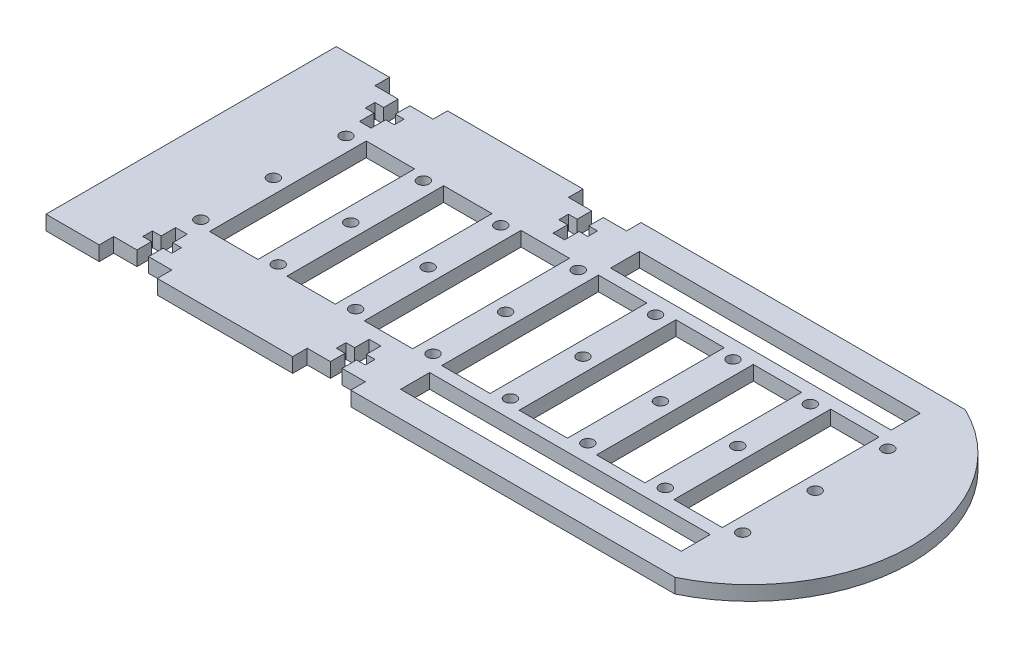
SolidWorks part; units mm, degrees
ref_plane "Front Plane" through (0, 0, 0) normal (0, 0, 1) x (1, 0, 0)
ref_plane "Top Plane" through (0, 0, 0) normal (0, 1, 0) x (1, 0, 0)
ref_plane "Right Plane" through (0, 0, 0) normal (1, 0, 0) x (0, 0, -1)
sketch "Sketch2" plane through (0, 0, 0) normal (0, 1, 0) x (1, 0, 0)
  line L0 (-93.98, 0) -> (93.98, 0) construction
  line L2 (-93.98, 38.1) -> (-93.98, -38.1)
  line L3 (-93.98, -38.1) -> (71.12, -38.1)
  line L9 (-93.98, 38.1) -> (71.12, 38.1)
  arc A8 (71.12, 38.1) -> (71.12, -38.1) centre (52.8038, 0) cw
  dimension "D1" = 165.1
  dimension "D2" = 76.2
extrude "Boss-Extrude1" add sketch "Sketch2" along normal blind 3.81
sketch "Sketch4" plane through (0, 0, 0) normal (0, -1, 0) x (-1, 0, 0)
  line L0 (46.99, -35.56) -> (46.99, -29.7953) construction
  line L2 (93.98, 38.1) -> (93.98, -38.1) construction
  dimension "D1" = 46.99
sketch "Sketch8" plane through (0, 0, 38.1) normal (0, 0, 1) x (1, 0, 0)
  line L0 (-46.99, 0) -> (-46.99, 3.81) construction
  line L1 (-93.98, 3.81) -> (71.12, 3.81) construction
ref_plane "Plane1" through (-46.99, 0, 0) normal (1, 0, 0) x (0, 0, -1)
sketch "Sketch9" plane through (0, 0, 0) normal (0, -1, 0) x (1, 0, 0)
  line L0 (-72.39, 38.1) -> (-72.39, 27.94) construction
  line L1 (-93.98, 38.1) -> (71.12, 38.1) construction
  line L2 (-80.01, 38.1) -> (-80.01, 34.29)
  line L3 (-80.01, 34.29) -> (-73.914, 34.29)
  line L4 (-73.914, 34.29) -> (-73.914, 30.48)
  line L5 (-73.914, 30.48) -> (-76.2, 30.48)
  line L6 (-76.2, 30.48) -> (-76.2, 27.94)
  line L7 (-76.2, 27.94) -> (-73.914, 27.94)
  line L8 (-73.914, 27.94) -> (-73.914, 24.13)
  line L9 (-73.914, 24.13) -> (-70.866, 24.13)
  line L10 (-46.99, 35.56) -> (-46.99, 29.7953) construction
  line L11 (-70.866, 34.29) -> (-70.866, 30.48)
  line L12 (-70.866, 27.94) -> (-70.866, 24.13)
  line L13 (-68.58, 27.94) -> (-70.866, 27.94)
  line L14 (-68.58, 30.48) -> (-68.58, 27.94)
  line L15 (-70.866, 30.48) -> (-68.58, 30.48)
  line L16 (-64.77, 34.29) -> (-70.866, 34.29)
  line L17 (-64.77, 38.1) -> (-64.77, 34.29)
  point P19 (-72.39, 24.13)
  dimension "D1" = 7.62
  dimension "D2" = 3.048
  dimension "D3" = 7.62
  dimension "D4" = 3.81
  dimension "D5" = 3.81
  dimension "D6" = 2.54
  dimension "D7" = 13.97
  dimension "D8" = 25.4
extrude "Cut-Extrude8" cut sketch "Sketch9" against normal through all and the other way through all flip side to cut
mirror "Mirror5" about plane through (-46.99, 0, 0) normal (1, 0, 0) of "Cut-Extrude8"
mirror "Mirror6" about plane through (0, 0, 0) normal (0, 0, 1) of "Mirror5", "Cut-Extrude8"
sketch "Sketch5" plane through (0, 0, 0) normal (0, -1, 0) x (1, 0, 0)
  line L0 (-93.98, 0) -> (0, 0) construction
  line L1 (-93.98, -38.1) -> (-93.98, 38.1) construction
  line L3 (-93.98, 38.1) -> (-80.01, 38.1) construction
  circle A0 centre (-72.39, 19.05) radius 1.524
  dimension "D1" = 3.048
  dimension "D2" = 19.05
  dimension "D3" = 21.59
extrude "Cut-Extrude2" cut sketch "Sketch5" against normal through all
pattern_linear "LPattern1" count 3 spacing 19.05 along (0, 0, -1) count 8 spacing 20.32 along (1, 0, 0) of "Cut-Extrude2"
sketch "Sketch6" plane through (0, 0, 0) normal (0, -1, 0) x (1, 0, 0)
  line L0 (8.89, 19.05) -> (29.21, 19.05) construction
  line L1 (8.89, -19.05) -> (29.21, -19.05) construction
  line L2 (-21.59, 20.574) -> (-21.59, -20.574) construction
  line L3 (-27.94, 20.574) -> (-15.24, 20.574)
  line L4 (-27.94, 20.574) -> (-27.94, -20.574)
  line L5 (-27.94, -20.574) -> (-15.24, -20.574)
  line L6 (-15.24, 20.574) -> (-15.24, -20.574)
  line L7 (-31.75, 0) -> (-11.43, 0) construction
  point P4 (-21.59, 0)
  point P13 (-21.59, 0)
  dimension "D1" = 41.148
  dimension "D2" = 12.7
extrude "Cut-Extrude5" cut sketch "Sketch6" against normal through all
pattern_linear "LPattern2" count 3 spacing 20.32 along (-1, 0, 0) of "Cut-Extrude5"
pattern_linear "LPattern3" count 5 spacing 20.32 along (1, 0, 0) of "Cut-Extrude5"
sketch "Sketch7" plane through (0, 0, 0) normal (0, -1, 0) x (1, 0, 0)
  line L0 (-7.62, 20.574) -> (-7.62, -20.574) construction
  line L1 (-7.62, 31.369) -> (66.04, 31.369)
  line L2 (-7.62, 31.369) -> (-7.62, 23.749)
  line L3 (-7.62, 23.749) -> (66.04, 23.749)
  line L4 (66.04, 31.369) -> (66.04, 23.749)
  line L8 (-93.98, 0) -> (-88.4319, 0) construction
  line L9 (-93.98, -38.1) -> (-93.98, 38.1) construction
  line L21 (66.04, -20.574) -> (66.04, 20.574) construction
  dimension "D1" = 7.62
extrude "Cut-Extrude6" cut sketch "Sketch7" against normal through all
mirror "Mirror3" about plane through (0, 0, 0) normal (0, 0, 1) of "Cut-Extrude6"
